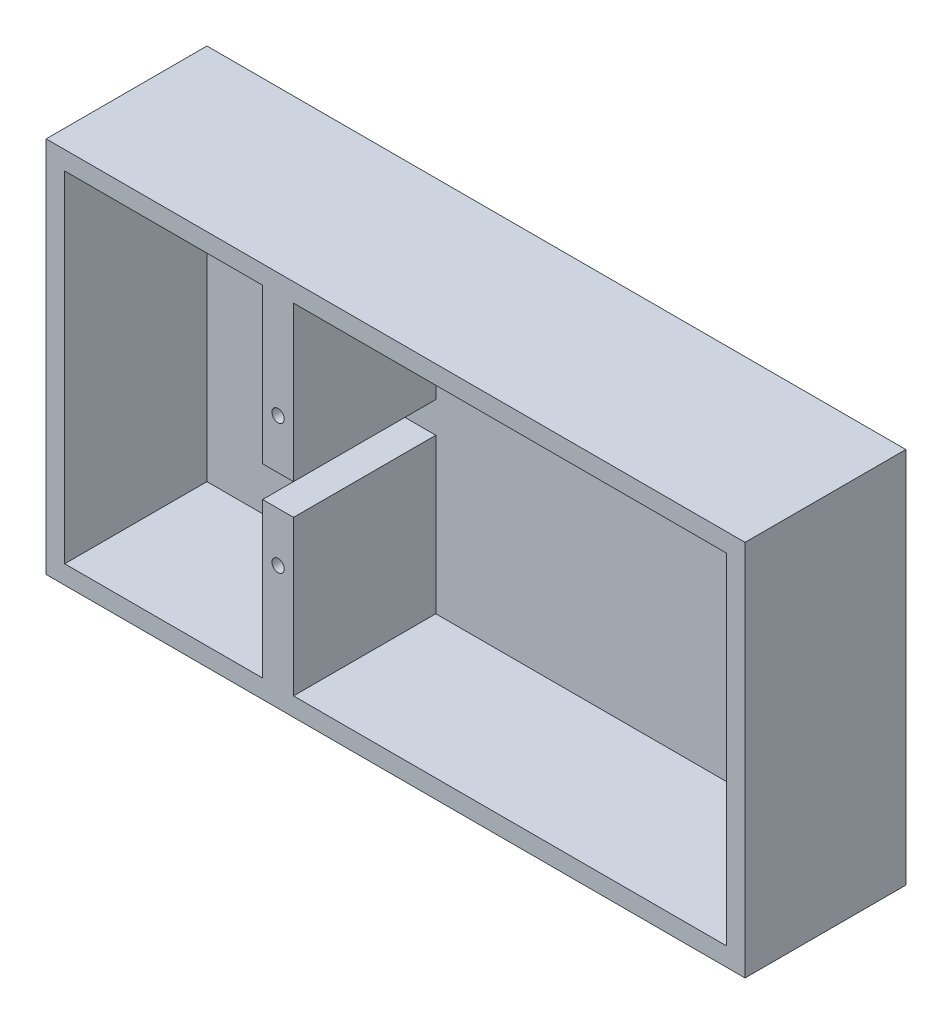
SolidWorks part; units mm, degrees
ref_plane "Front Plane" through (0, 0, 0) normal (0, 0, 1) x (1, 0, 0)
ref_plane "Top Plane" through (0, 0, 0) normal (0, 1, 0) x (1, 0, 0)
ref_plane "Right Plane" through (0, 0, 0) normal (1, 0, 0) x (0, 0, -1)
sketch "Sketch1" plane through (0, 0, 0) normal (0, 0, 1) x (1, 0, 0)
  line L1 (-73, 58) -> (-3, 58)
  line L2 (-73, 58) -> (-73, 3)
  line L3 (-73, 3) -> (-3, 3)
  line L4 (-3, 58) -> (-3, 3)
  line L5 (-110, 58) -> (-78, 58)
  line L6 (-110, 58) -> (-110, 3)
  line L7 (-110, 3) -> (-78, 3)
  line L8 (-78, 58) -> (-78, 3)
  line L9 (-113, 61) -> (0, 61)
  line L10 (-113, 61) -> (-113, 0)
  line L11 (-113, 0) -> (0, 0)
  line L12 (0, 61) -> (0, 0)
  dimension "D1" = 55
  dimension "D2" = 70
  dimension "D3" = 32
  dimension "D4" = 55
  dimension "D5" = 5
  dimension "D6" = 3
  dimension "D7" = 3
  dimension "D8" = 3
  dimension "D9" = 3
extrude "Boss-Extrude1" add sketch "Sketch1" along normal blind 26
sketch "Sketch2" plane through (0, 0, 0) normal (0, 0, -1) x (-1, 0, 0)
  line L0 (3, 3) -> (3, 58) construction
  line L1 (3, 58) -> (73, 58) construction
  line L2 (73, 58) -> (73, 3) construction
  line L3 (73, 3) -> (3, 3) construction
  line L4 (110, 3) -> (78, 3) construction
  line L5 (78, 3) -> (78, 58) construction
  line L6 (110, 58) -> (110, 3) construction
  line L7 (78, 58) -> (110, 58) construction
  line L8 (3, 3) -> (3, 58)
  line L9 (3, 58) -> (73, 58)
  line L10 (73, 58) -> (73, 3)
  line L11 (73, 3) -> (3, 3)
  line L12 (110, 3) -> (78, 3)
  line L13 (78, 3) -> (78, 58)
  line L14 (110, 58) -> (110, 3)
  line L15 (78, 58) -> (110, 58)
extrude "Boss-Extrude2" add sketch "Sketch2" against normal blind 3
sketch "Sketch3" plane through (-73, 0, 0) normal (1, 0, 0) x (0, 0, -1)
  line L0 (-26, 58) -> (-26, 3) construction
  line L1 (-26, 28) -> (-3, 28)
  line L2 (-26, 28) -> (-26, 33)
  line L3 (-26, 33) -> (-3, 33)
  line L4 (-3, 28) -> (-3, 33)
  line L5 (-3, 3) -> (-3, 58) construction
  point P8 (-26, 30.5)
  dimension "D1" = 5
  dimension "D2" = 27.5
extrude "Cut-Extrude1" cut sketch "Sketch3" against normal blind 5
sketch "Sketch5" plane through (0, 0, 0) normal (0, -1, 0) x (-1, 0, 0)
  line L0 (113, 0) -> (0, 0) construction
  line L1 (0, -26) -> (0, 0) construction
  circle A0 centre (12.5, -8) radius 4
  dimension "D1" = 8
  dimension "D2" = 8
  dimension "D3" = 12.5
extrude "Cut-Extrude3" cut sketch "Sketch5" against normal blind 10
sketch "Sketch6" plane through (0, 0, 26) normal (0, 0, 1) x (1, 0, 0)
  line L0 (0, 61) -> (-113, 61) construction
  line L1 (0, 0) -> (0, 61) construction
  line L4 (-113, 0) -> (0, 0) construction
  circle A0 centre (-75.5, 41) radius 1
  circle A1 centre (-75.5, 20) radius 1
  dimension "D4" = 2
  dimension "D5" = 2
  dimension "D1" = 20
  dimension "D2" = 20
  dimension "D3" = 75.5
extrude "Cut-Extrude4" cut sketch "Sketch6" against normal blind 30
